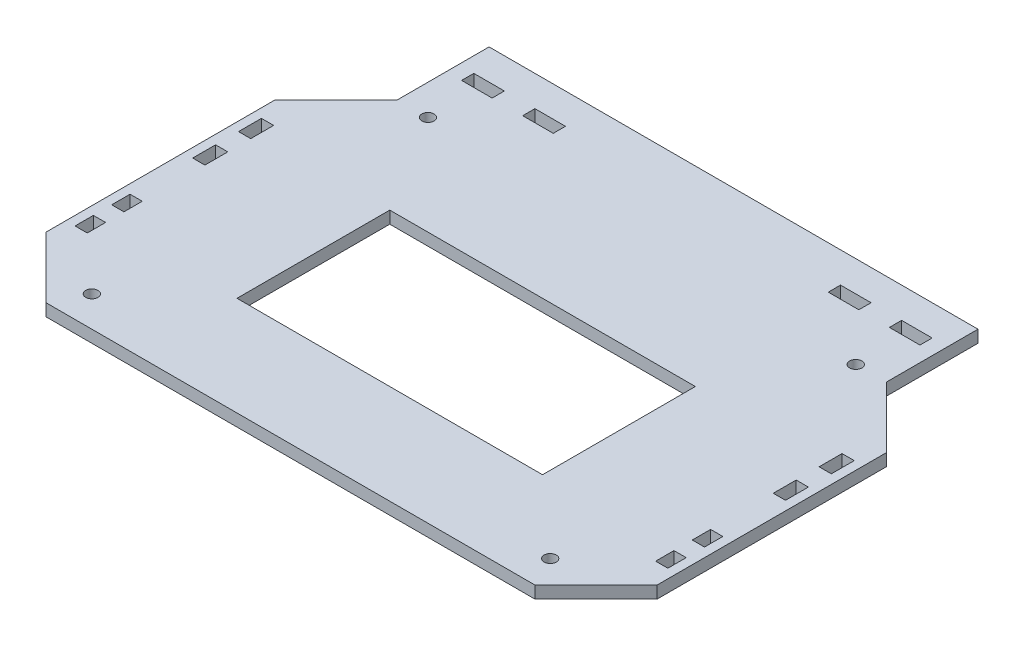
SolidWorks part; units mm, degrees
ref_plane "Front Plane" through (0, 0, 0) normal (0, 0, 1) x (1, 0, 0)
ref_plane "Top Plane" through (0, 0, 0) normal (0, 1, 0) x (1, 0, 0)
ref_plane "Right Plane" through (0, 0, 0) normal (1, 0, 0) x (0, 0, -1)
sketch "Sketch1" plane through (0, 0, 0) normal (0, 1, 0) x (1, 0, 0)
  line L0 (-100, -71) -> (-240.272, -71) construction
  line L1 (0, -125) -> (0, -127.13) construction
  line L2 (178.4753, 0) -> (-178.4753, 0) construction
  line L3 (-73, -115) -> (-80, -115) construction
  line L4 (133.1028, -10) -> (-130.8248, -10) construction
  line L5 (124.9013, -67.5) -> (-188.6886, -67.5) construction
  line L6 (-80, -10) -> (-80, 10)
  line L7 (50, -42.5) -> (-50, -42.5)
  line L8 (-50, -42.5) -> (-50, -92.5)
  line L9 (-50, -92.5) -> (50, -92.5)
  line L10 (50, -92.5) -> (50, -42.5)
  line L15 (80, -10) -> (80, 10)
  line L19 (100, -105) -> (100, -30)
  line L20 (100, -105) -> (80, -125)
  line L21 (80, -10) -> (100, -30)
  line L22 (-80, -10) -> (-100, -30)
  line L23 (-100, -105) -> (-80, -125)
  line L24 (-100, -105) -> (-100, -30)
  line L25 (80, -125) -> (-80, -125)
  line L32 (0, 0) -> (0, 15) construction
  line L34 (0, 0) -> (0, -60) construction
  line L40 (80, -75) -> (80, -115) construction
  line L41 (80, -115) -> (73, -115) construction
  line L42 (-80, -115) -> (-80, -75) construction
  line L43 (128.2099, -71) -> (100, -71) construction
  line L44 (97, -37.5) -> (97, -45)
  line L45 (97, -92.5) -> (97, -98.5)
  line L46 (75, 10) -> (65, 10)
  line L47 (93, -45) -> (93, -37.5)
  line L48 (97, -52.5) -> (97, -60)
  line L49 (97, -37.5) -> (93, -37.5)
  line L50 (97, -45) -> (93, -45)
  line L51 (97, -98.5) -> (93, -98.5)
  line L52 (93, -52.5) -> (97, -52.5)
  line L53 (97, -60) -> (93, -60)
  line L54 (93, -98.5) -> (93, -92.5)
  line L55 (93, -92.5) -> (97, -92.5)
  line L56 (55, 6) -> (45, 6)
  line L57 (97, -86.5) -> (93, -86.5)
  line L58 (93, -86.5) -> (93, -80.5)
  line L59 (93, -80.5) -> (97, -80.5)
  line L60 (93, -60) -> (93, -52.5)
  line L61 (97, -80.5) -> (97, -86.5)
  line L62 (-93, -98.5) -> (-93, -92.5)
  line L63 (-97, -98.5) -> (-93, -98.5)
  line L64 (-97, -92.5) -> (-97, -98.5)
  line L65 (-93, -92.5) -> (-97, -92.5)
  line L66 (-93, -86.5) -> (-93, -80.5)
  line L67 (-97, -86.5) -> (-93, -86.5)
  line L68 (-97, -80.5) -> (-97, -86.5)
  line L69 (-93, -80.5) -> (-97, -80.5)
  line L70 (-97, -60) -> (-93, -60)
  line L71 (-93, -60) -> (-93, -52.5)
  line L72 (-97, -52.5) -> (-97, -60)
  line L73 (-93, -52.5) -> (-97, -52.5)
  line L74 (-97, -45) -> (-93, -45)
  line L75 (-93, -45) -> (-93, -37.5)
  line L76 (-97, -37.5) -> (-93, -37.5)
  line L77 (-97, -37.5) -> (-97, -45)
  line L78 (-45, 6) -> (-55, 6)
  line L79 (75, 10) -> (75, 6)
  line L80 (65, 10) -> (65, 6)
  line L81 (55, 6) -> (55, 10)
  line L82 (45, 10) -> (45, 6)
  line L83 (55, 10) -> (45, 10)
  line L84 (-65, 6) -> (-75, 6)
  line L85 (-75, 10) -> (-75, 6)
  line L86 (-75, 10) -> (-65, 10)
  line L87 (-65, 10) -> (-65, 6)
  line L88 (-55, 6) -> (-55, 10)
  line L89 (80, 10) -> (80, 20)
  line L90 (-45, 10) -> (-45, 6)
  line L91 (-55, 10) -> (-45, 10)
  line L92 (75, 6) -> (65, 6)
  line L93 (80, 20) -> (-80, 20)
  line L94 (-80, 20) -> (-80, 10)
  circle A16 centre (-75, -115) radius 2
  circle A17 centre (-70, -10) radius 2
  circle A18 centre (75, -115) radius 2
  circle A19 centre (70, -10) radius 2
  point P6 (0, 0)
  point P53 (80, 0)
  point P55 (-80, 0)
  point P59 (50, -70)
  point P66 (-50, -70)
  point P71 (0, 15)
  point P82 (-30, 30)
  point P83 (30, 30)
  point P85 (30, -50)
  point P86 (-30, -50)
  point P94 (-30, 30)
  point P116 (95, -86.5)
  dimension "D8" = 25
  dimension "D9" = 25
  dimension "D22" = 4
  dimension "D24" = 5
  dimension "D26" = 10
  dimension "D5" = 10
  dimension "D6" = 263.9276
  dimension "D7" = 57.5
  dimension "D10" = 50
  dimension "D11" = 10
  dimension "D12" = 50
  dimension "D14" = 15
  dimension "D18" = 20
  dimension "D19" = 160
  dimension "D23" = 10
  dimension "D25" = 5
  dimension "D27" = 10
  dimension "D28" = 3
  dimension "D29" = 5
  dimension "D31" = 7.5
  dimension "D32" = 7.5
  dimension "D33" = 7.5
  dimension "D34" = 6
  dimension "D35" = 6
  dimension "D36" = 6
  dimension "D37" = 10
  dimension "D38" = 10
  dimension "D40" = 4
extrude "Boss-Extrude1" add sketch "Sketch1" along normal blind 4
sketch "Sketch2" plane through (0, 0, 0) normal (0, -1, 0) x (1, 0, 0)
  text T0 "EOT" font "Times New Roman" height 10
extrude "Cut-Extrude2" cut sketch "Sketch2" against normal blind 2
